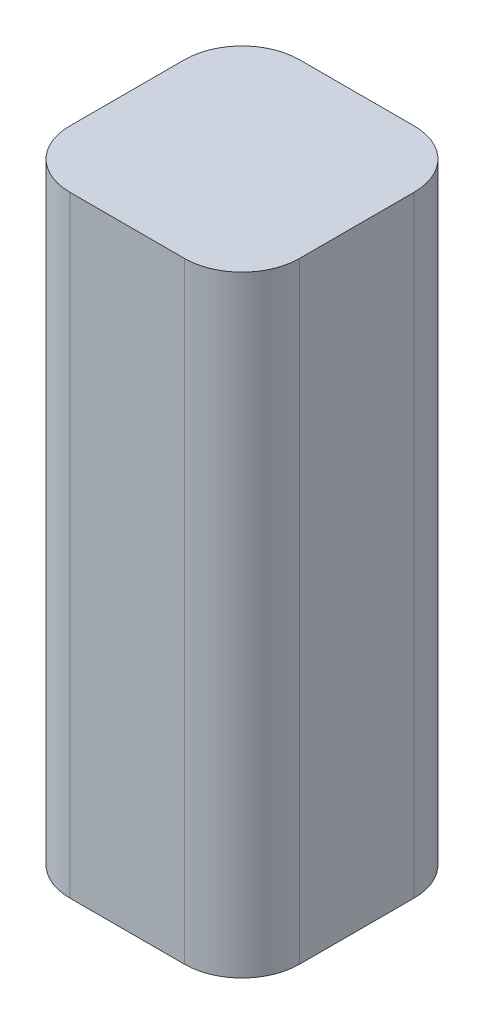
SolidWorks part; units mm, degrees
ref_plane "前基準面" through (0, 0, 0) normal (0, 0, 1) x (1, 0, 0)
ref_plane "上基準面" through (0, 0, 0) normal (0, 1, 0) x (1, 0, 0)
ref_plane "右基準面" through (0, 0, 0) normal (1, 0, 0) x (0, 0, -1)
sketch "草圖1" plane through (0, 0, 0) normal (0, 1, 0) x (1, 0, 0)
  line L1 (-4, 4) -> (4, 4)
  line L2 (-4, 4) -> (-4, -4)
  line L3 (-4, -4) -> (4, -4)
  line L4 (4, 4) -> (4, -4)
  line L5 (-4, 4) -> (4, -4) construction
  line L6 (-4, -4) -> (4, 4) construction
  circle A0 centre (0, 0) radius 3.05
  point P0 (0, 0)
  dimension "D1" = 6.1
  dimension "D2" = 4
  dimension "D3" = 4
extrude "填料-伸長1" add sketch "草圖1" along normal blind 8.8
sketch "草圖2" plane through (0, 0, -4) normal (0, 0, -1) x (-1, 0, 0)
  line L0 (-4, 8.8) -> (-4, 13.3) construction
  line L1 (4, 8.8) -> (4, 0) construction
  line L3 (-4, 8.8) -> (4, 8.8)
  line L4 (-4, 8.8) -> (-4, 13.3)
  line L5 (-4, 13.3) -> (4, 13.3)
  line L6 (4, 8.8) -> (4, 13.3)
  dimension "D1" = 4.5
  dimension "D2" = 8.8
extrude "填料-伸長2" add sketch "草圖2" against normal blind 8.8
sketch "草圖3" plane through (0, 8.8, 0) normal (0, -1, 0) x (1, 0, 0)
  circle A0 centre (0, 0) radius 3.05
extrude "除料-伸長1" cut sketch "草圖3" against normal through all
sketch "草圖4" plane through (0, 8.8, 0) normal (0, -1, 0) x (1, 0, 0)
  line L1 (-4, 4) -> (4, 4)
  line L2 (-4, 4) -> (-4, 4.8)
  line L3 (-4, 4.8) -> (4, 4.8)
  line L4 (4, 4) -> (4, 4.8)
extrude "除料-伸長2" cut sketch "草圖4" against normal through all
sketch "草圖5" plane through (-4, 0, 0) normal (-1, 0, 0) x (0, 0, 1)
  line L1 (4, 13.3) -> (-4, 13.3) construction
  line L2 (2.8973, 13.3) -> (2.8973, 12.8) construction
  line L3 (1.3074, 12) -> (-1.3074, 12)
  line L4 (1.3074, 12) -> (1.3074, 12.8)
  line L5 (1.3074, 12.8) -> (-1.3074, 12.8)
  line L6 (-1.3074, 12) -> (-1.3074, 12.8)
  line L7 (1.3074, 12) -> (-1.3074, 12.8) construction
  line L8 (1.3074, 12.8) -> (-1.3074, 12) construction
  line L9 (-997.1027, 12.8) -> (49002.8973, 12.8) construction
  point P0 (0, 12.4)
  dimension "D1" = 0
  dimension "D2" = 0.8
  dimension "D5" = 0.5
extrude "除料-伸長3" cut sketch "草圖5" against normal blind 6
sketch "草圖8" plane through (0, 13.3, 0) normal (0, 1, 0) x (1, 0, 0)
  line L1 (-4, -4) -> (4, -4)
  line L2 (-4, -4) -> (-4, 4)
  line L3 (-4, 4) -> (4, 4)
  line L4 (4, -4) -> (4, 4)
  line L5 (-4, -4) -> (4, 4) construction
  line L6 (-4, 4) -> (4, -4) construction
  point P0 (0, 0)
extrude "填料-伸長3" add sketch "草圖8" along normal blind 8
fillet "圓角2" radius 2 4 edges at (4, 10.65, -4) (4, 10.65, 4) (-4, 10.65, -4) (-4, 10.65, 4)
